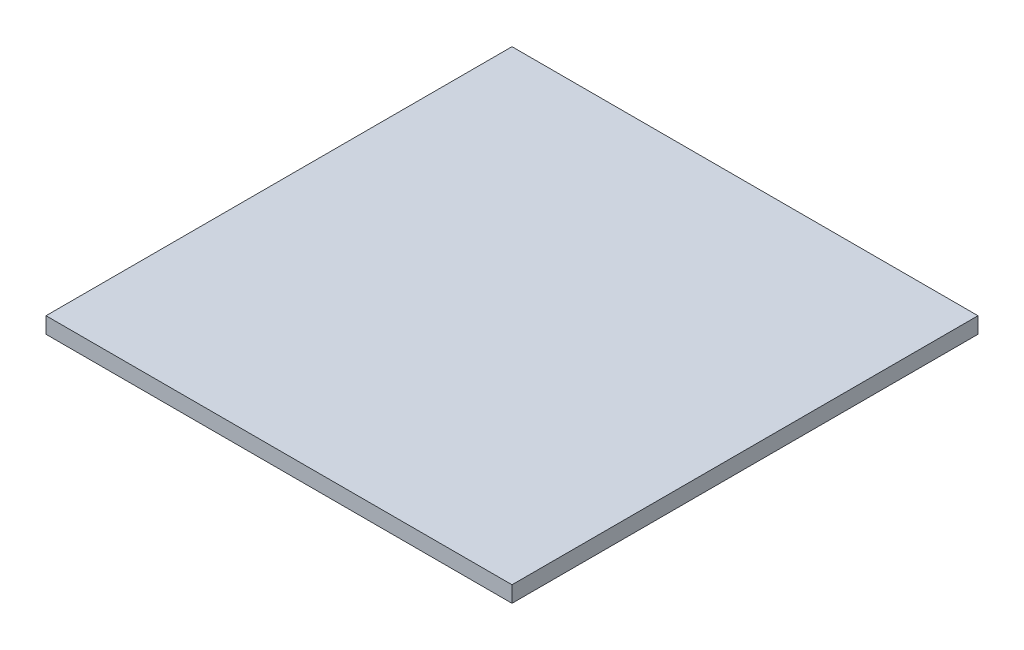
SolidWorks part; units mm, degrees
ref_plane "Front Plane" through (0, 0, 0) normal (0, 0, 1) x (1, 0, 0)
ref_plane "Top Plane" through (0, 0, 0) normal (0, 1, 0) x (1, 0, 0)
ref_plane "Right Plane" through (0, 0, 0) normal (1, 0, 0) x (0, 0, -1)
sketch "Sketch1" plane through (0, 0, 0) normal (0, 1, 0) x (1, 0, 0)
  line L1 (77.216, 77.216) -> (-77.216, 77.216)
  line L2 (77.216, 77.216) -> (77.216, -77.216)
  line L3 (77.216, -77.216) -> (-77.216, -77.216)
  line L4 (-77.216, 77.216) -> (-77.216, -77.216)
  line L5 (77.216, 77.216) -> (-77.216, -77.216) construction
  line L6 (77.216, -77.216) -> (-77.216, 77.216) construction
  point P0 (0, 0)
  dimension "D1" = 154.432
  dimension "D2" = 154.432
extrude "Boss-Extrude1" add sketch "Sketch1" along normal blind 5.334
equation "\"material\"= \"GMaterial@MotorizedPlatform.assembly\""
equation "\"D1@Boss-Extrude1\"=\"material\""
equation "\"D1@Sketch1\" = 6.5 - (\"material\" * 2)"
equation "\"D2@Sketch1\" = 6.5 - (\"material\" * 2)"
